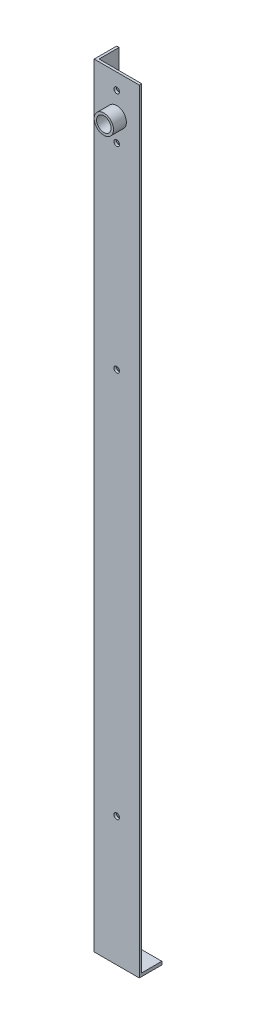
SolidWorks part; units mm, degrees
material "Galvanized Steel"
ref_plane "Front Plane" through (0, 0, 0) normal (0, 0, 1) x (1, 0, 0)
ref_plane "Top Plane" through (0, 0, 0) normal (0, 1, 0) x (1, 0, 0)
ref_plane "Right Plane" through (0, 0, 0) normal (1, 0, 0) x (0, 0, -1)
sketch "Sketch1" plane through (0, 0, 0) normal (0, 1, 0) x (1, 0, 0)
  line L1 (-44.45, -22.225) -> (44.45, -22.225)
  line L2 (-44.45, -22.225) -> (-44.45, 22.225)
  line L3 (-44.45, 22.225) -> (44.45, 22.225)
  line L4 (44.45, -22.225) -> (44.45, 22.225)
  line L5 (-44.45, -22.225) -> (44.45, 22.225) construction
  line L6 (-44.45, 22.225) -> (44.45, -22.225) construction
  point P0 (0, 0)
  dimension "D1" = 88.9
  dimension "D2" = 44.45
extrude "Boss-Extrude1" add sketch "Sketch1" along normal blind 1524
sketch "Sketch2" plane through (0, 0, 22.225) normal (0, 0, 1) x (1, 0, 0)
  line L0 (-44.45, 1524) -> (44.45, 1524) construction
  line L2 (-44.45, 0) -> (44.45, 0) construction
  line L3 (0, 1402.7547) -> (0, 1492.8453) construction
  circle A0 centre (0, 1447.8) radius 7.9375
  circle A1 centre (0, 1016) radius 5.588
  circle A2 centre (0, 254) radius 5.588
  circle A4 centre (0, 1492.8453) radius 5.588
  circle A5 centre (0, 1402.7547) radius 5.588
  point P5 (0, 1524)
  point P15 (0, 1447.8)
  dimension "D1" = 15.875
  dimension "D4" = 11.176
  dimension "D7" = 11.176
  dimension "D2" = 1447.8
  dimension "D3" = 508
  dimension "D5" = 254
  dimension "D6" = 90.0906
extrude "Cut-Extrude1" cut sketch "Sketch2" against normal up to next
sketch "Sketch4" plane through (0, 0, 22.225) normal (0, 0, 1) x (1, 0, 0)
  circle A0 centre (0, 1447.8) radius 14.2875
  circle A1 centre (0, 1447.8) radius 19.05
  dimension "D1" = 38.1
  dimension "D2" = 28.575
extrude "Boss-Extrude2" add sketch "Sketch4" along normal blind 25.4
sketch "Sketch5" plane through (0, 1524, 0) normal (0, 1, 0) x (1, 0, 0)
  line L4 (-39.6875, 17.4625) -> (-39.6875, 22.225)
  line L5 (44.45, 22.225) -> (-44.45, 22.225) construction
  line L6 (-39.6875, 22.225) -> (44.45, 22.225)
  line L7 (44.45, 22.225) -> (44.45, -17.4625)
  line L9 (39.6875, -17.4625) -> (39.6875, 17.4625)
  line L20 (39.6875, 17.4625) -> (-39.6875, 17.4625)
  line L32 (-39.6875, 17.4625) -> (-39.6875, -17.4625)
  line L33 (-39.6875, -17.4625) -> (39.6875, -17.4625)
  line L36 (-39.6875, 17.4625) -> (-39.6875, -17.4625)
  line L37 (-39.6875, -17.4625) -> (39.6875, -17.4625)
  line L38 (44.45, -22.225) -> (44.45, 22.225) construction
  line L39 (44.45, -17.4625) -> (39.6875, -17.4625)
  dimension "D1" = 4.7625
extrude "Cut-Extrude3" cut sketch "Sketch5" against normal up to next
sketch "Sketch7" plane through (0, 0, 0) normal (0, -1, 0) x (1, 0, 0)
  line L1 (-44.45, -22.225) -> (44.45, -22.225)
  line L2 (-44.45, -22.225) -> (-44.45, 22.225)
  line L3 (-44.45, 22.225) -> (44.45, 22.225)
  line L4 (44.45, -22.225) -> (44.45, 22.225)
extrude "Boss-Extrude3" add sketch "Sketch7" against normal blind 6.35
